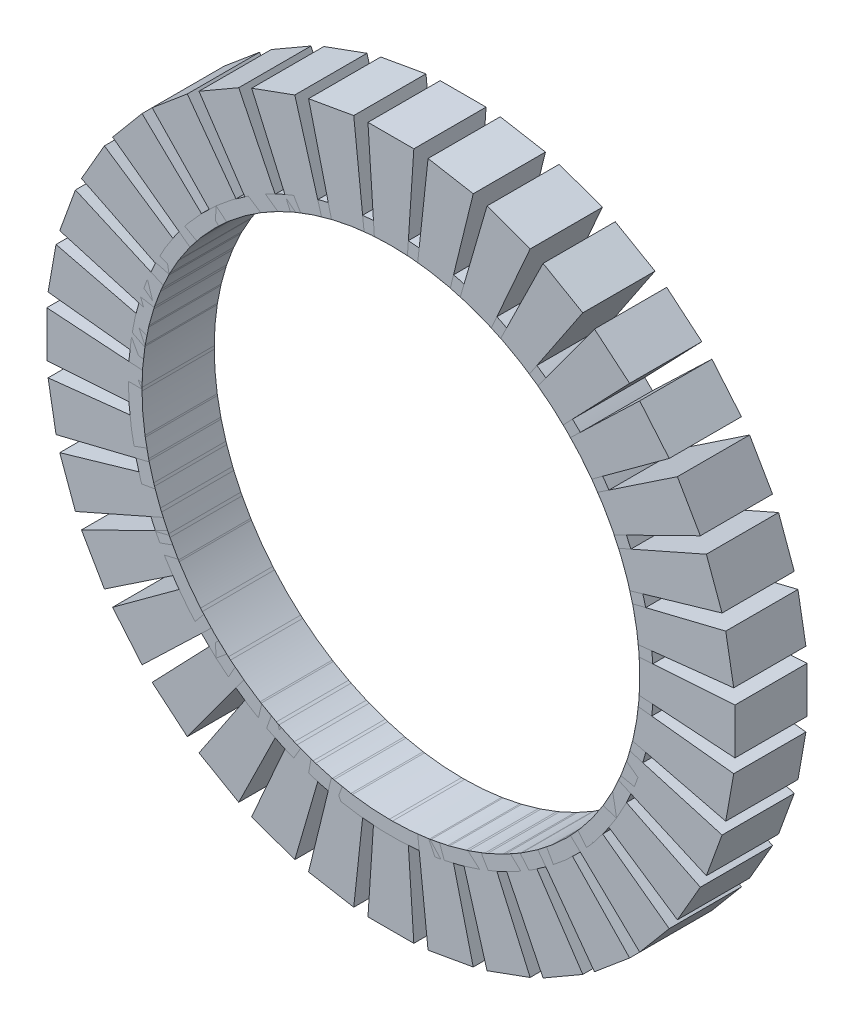
SolidWorks part; units mm, degrees
ref_plane "Front Plane" through (0, 0, 0) normal (0, 0, 1) x (1, 0, 0)
ref_plane "Top Plane" through (0, 0, 0) normal (0, 1, 0) x (1, 0, 0)
ref_plane "Right Plane" through (0, 0, 0) normal (1, 0, 0) x (0, 0, -1)
sketch "Sketch1" plane through (0, 0, 0) normal (0, 0, 1) x (1, 0, 0)
  line L0 (0, 0) -> (0, 40.5) construction
  line L1 (0, 0) -> (7.0328, 39.8847) construction
  line L2 (0, 0) -> (13.8518, 38.0576) construction
  line L3 (0, 0) -> (20.25, 35.074) construction
  line L4 (0, 0) -> (26.0329, 31.0248) construction
  line L5 (0, 0) -> (31.0248, 26.0329) construction
  line L6 (0, 0) -> (35.074, 20.25) construction
  line L7 (0, 0) -> (38.0576, 13.8518) construction
  line L8 (0, 0) -> (39.8847, 7.0328) construction
  line L9 (0, 0) -> (40.5, 0) construction
  line L10 (0, 0) -> (39.8847, -7.0328) construction
  line L11 (0, 0) -> (38.0576, -13.8518) construction
  line L12 (0, 0) -> (35.074, -20.25) construction
  line L13 (0, 0) -> (31.0248, -26.0329) construction
  line L14 (0, 0) -> (26.0329, -31.0248) construction
  line L15 (0, 0) -> (20.25, -35.074) construction
  line L16 (0, 0) -> (13.8518, -38.0576) construction
  line L17 (0, 0) -> (7.0328, -39.8847) construction
  line L18 (0, 0) -> (0, -40.5) construction
  line L19 (0, 0) -> (-7.0328, -39.8847) construction
  line L20 (0, 0) -> (-13.8518, -38.0576) construction
  line L21 (0, 0) -> (-20.25, -35.074) construction
  line L22 (0, 0) -> (-26.0329, -31.0248) construction
  line L23 (0, 0) -> (-31.0248, -26.0329) construction
  line L24 (0, 0) -> (-35.074, -20.25) construction
  line L25 (0, 0) -> (-38.0576, -13.8518) construction
  line L26 (0, 0) -> (-39.8847, -7.0328) construction
  line L27 (0, 0) -> (-40.5, 0) construction
  line L28 (0, 0) -> (-39.8847, 7.0328) construction
  line L29 (0, 0) -> (-38.0576, 13.8518) construction
  line L30 (0, 0) -> (-35.074, 20.25) construction
  line L31 (0, 0) -> (-31.0248, 26.0329) construction
  line L32 (0, 0) -> (-26.0329, 31.0248) construction
  line L33 (0, 0) -> (-20.25, 35.074) construction
  line L34 (0, 0) -> (-13.8518, 38.0576) construction
  line L35 (0, 0) -> (-7.0328, 39.8847) construction
  line L36 (-2.7, 40.5) -> (2.7, 40.5)
  line L37 (-1.949, 29.2351) -> (-2.7, 40.5)
  line L38 (1.949, 29.2351) -> (2.7, 40.5)
  line L39 (0, 0) -> (-1.949, 29.2351) construction
  line L40 (0, 0) -> (1.949, 29.2351) construction
  line L41 (3.1572, 29.1294) -> (4.3738, 40.3536)
  line L42 (6.996, 28.4525) -> (9.6917, 39.4159)
  line L43 (4.3738, 40.3536) -> (9.6917, 39.4159)
  line L44 (8.1675, 28.1386) -> (11.3146, 38.981)
  line L45 (11.8305, 26.8054) -> (16.389, 37.1341)
  line L46 (11.3146, 38.981) -> (16.389, 37.1341)
  line L47 (12.9297, 26.2928) -> (17.9117, 36.424)
  line L48 (16.3054, 24.3438) -> (22.5883, 33.724)
  line L49 (17.9117, 36.424) -> (22.5883, 33.724)
  line L50 (17.2989, 23.6482) -> (23.9646, 32.7603)
  line L51 (20.285, 21.1426) -> (28.1012, 29.2893)
  line L52 (23.9646, 32.7603) -> (28.1012, 29.2893)
  line L53 (21.1426, 20.285) -> (29.2893, 28.1012)
  line L54 (23.6482, 17.2989) -> (32.7603, 23.9646)
  line L55 (29.2893, 28.1012) -> (32.7603, 23.9646)
  line L56 (24.3438, 16.3054) -> (33.724, 22.5883)
  line L57 (26.2928, 12.9297) -> (36.424, 17.9117)
  line L58 (33.724, 22.5883) -> (36.424, 17.9117)
  line L59 (26.8054, 11.8305) -> (37.1341, 16.389)
  line L60 (28.1386, 8.1675) -> (38.981, 11.3146)
  line L61 (37.1341, 16.389) -> (38.981, 11.3146)
  line L62 (28.4525, 6.996) -> (39.4159, 9.6917)
  line L63 (29.1294, 3.1572) -> (40.3536, 4.3738)
  line L64 (39.4159, 9.6917) -> (40.3536, 4.3738)
  line L65 (29.2351, 1.949) -> (40.5, 2.7)
  line L66 (29.2351, -1.949) -> (40.5, -2.7)
  line L67 (40.5, 2.7) -> (40.5, -2.7)
  line L68 (29.1294, -3.1572) -> (40.3536, -4.3738)
  line L69 (28.4525, -6.996) -> (39.4159, -9.6917)
  line L70 (40.3536, -4.3738) -> (39.4159, -9.6917)
  line L71 (28.1386, -8.1675) -> (38.981, -11.3146)
  line L72 (26.8054, -11.8305) -> (37.1341, -16.389)
  line L73 (38.981, -11.3146) -> (37.1341, -16.389)
  line L74 (26.2928, -12.9297) -> (36.424, -17.9117)
  line L75 (24.3438, -16.3054) -> (33.724, -22.5883)
  line L76 (36.424, -17.9117) -> (33.724, -22.5883)
  line L77 (23.6482, -17.2989) -> (32.7603, -23.9646)
  line L78 (21.1426, -20.285) -> (29.2893, -28.1012)
  line L79 (32.7603, -23.9646) -> (29.2893, -28.1012)
  line L80 (20.285, -21.1426) -> (28.1012, -29.2893)
  line L81 (17.2989, -23.6482) -> (23.9646, -32.7603)
  line L82 (28.1012, -29.2893) -> (23.9646, -32.7603)
  line L83 (16.3054, -24.3438) -> (22.5883, -33.724)
  line L84 (12.9297, -26.2928) -> (17.9117, -36.424)
  line L85 (22.5883, -33.724) -> (17.9117, -36.424)
  line L86 (11.8305, -26.8054) -> (16.389, -37.1341)
  line L87 (8.1675, -28.1386) -> (11.3146, -38.981)
  line L88 (16.389, -37.1341) -> (11.3146, -38.981)
  line L89 (6.996, -28.4525) -> (9.6917, -39.4159)
  line L90 (3.1572, -29.1294) -> (4.3738, -40.3536)
  line L91 (9.6917, -39.4159) -> (4.3738, -40.3536)
  line L92 (1.949, -29.2351) -> (2.7, -40.5)
  line L93 (-1.949, -29.2351) -> (-2.7, -40.5)
  line L94 (2.7, -40.5) -> (-2.7, -40.5)
  line L95 (-3.1572, -29.1294) -> (-4.3738, -40.3536)
  line L96 (-6.996, -28.4525) -> (-9.6917, -39.4159)
  line L97 (-4.3738, -40.3536) -> (-9.6917, -39.4159)
  line L98 (-8.1675, -28.1386) -> (-11.3146, -38.981)
  line L99 (-11.8305, -26.8054) -> (-16.389, -37.1341)
  line L100 (-11.3146, -38.981) -> (-16.389, -37.1341)
  line L101 (-12.9297, -26.2928) -> (-17.9117, -36.424)
  line L102 (-16.3054, -24.3438) -> (-22.5883, -33.724)
  line L103 (-17.9117, -36.424) -> (-22.5883, -33.724)
  line L104 (-17.2989, -23.6482) -> (-23.9646, -32.7603)
  line L105 (-20.285, -21.1426) -> (-28.1012, -29.2893)
  line L106 (-23.9646, -32.7603) -> (-28.1012, -29.2893)
  line L107 (-21.1426, -20.285) -> (-29.2893, -28.1012)
  line L108 (-23.6482, -17.2989) -> (-32.7603, -23.9646)
  line L109 (-29.2893, -28.1012) -> (-32.7603, -23.9646)
  line L110 (-24.3438, -16.3054) -> (-33.724, -22.5883)
  line L111 (-26.2928, -12.9297) -> (-36.424, -17.9117)
  line L112 (-33.724, -22.5883) -> (-36.424, -17.9117)
  line L113 (-26.8054, -11.8305) -> (-37.1341, -16.389)
  line L114 (-28.1386, -8.1675) -> (-38.981, -11.3146)
  line L115 (-37.1341, -16.389) -> (-38.981, -11.3146)
  line L116 (-28.4525, -6.996) -> (-39.4159, -9.6917)
  line L117 (-29.1294, -3.1572) -> (-40.3536, -4.3738)
  line L118 (-39.4159, -9.6917) -> (-40.3536, -4.3738)
  line L119 (-29.2351, -1.949) -> (-40.5, -2.7)
  line L120 (-29.2351, 1.949) -> (-40.5, 2.7)
  line L121 (-40.5, -2.7) -> (-40.5, 2.7)
  line L122 (-29.1294, 3.1572) -> (-40.3536, 4.3738)
  line L123 (-28.4525, 6.996) -> (-39.4159, 9.6917)
  line L124 (-40.3536, 4.3738) -> (-39.4159, 9.6917)
  line L125 (-28.1386, 8.1675) -> (-38.981, 11.3146)
  line L126 (-26.8054, 11.8305) -> (-37.1341, 16.389)
  line L127 (-38.981, 11.3146) -> (-37.1341, 16.389)
  line L128 (-26.2928, 12.9297) -> (-36.424, 17.9117)
  line L129 (-24.3438, 16.3054) -> (-33.724, 22.5883)
  line L130 (-36.424, 17.9117) -> (-33.724, 22.5883)
  line L131 (-23.6482, 17.2989) -> (-32.7603, 23.9646)
  line L132 (-21.1426, 20.285) -> (-29.2893, 28.1012)
  line L133 (-32.7603, 23.9646) -> (-29.2893, 28.1012)
  line L134 (-20.285, 21.1426) -> (-28.1012, 29.2893)
  line L135 (-17.2989, 23.6482) -> (-23.9646, 32.7603)
  line L136 (-28.1012, 29.2893) -> (-23.9646, 32.7603)
  line L137 (-16.3054, 24.3438) -> (-22.5883, 33.724)
  line L138 (-12.9297, 26.2928) -> (-17.9117, 36.424)
  line L139 (-22.5883, 33.724) -> (-17.9117, 36.424)
  line L140 (-11.8305, 26.8054) -> (-16.389, 37.1341)
  line L141 (-8.1675, 28.1386) -> (-11.3146, 38.981)
  line L142 (-16.389, 37.1341) -> (-11.3146, 38.981)
  line L143 (-6.996, 28.4525) -> (-9.6917, 39.4159)
  line L144 (-3.1572, 29.1294) -> (-4.3738, 40.3536)
  line L145 (-9.6917, 39.4159) -> (-4.3738, 40.3536)
  arc A0 (-18.8337, 22.4451) -> (14.65, 25.3745) centre (0, 0) ccw construction
  circle A1 centre (0, 0) radius 40.5 construction
  arc A2 (-1.949, 29.2351) -> (-5.0879, 28.8549) centre (0, 0) ccw construction
  arc A3 (-5.0879, 28.8549) -> (-10.0212, 27.533) centre (0, 0) ccw construction
  arc A4 (-10.0212, 27.533) -> (-14.65, 25.3745) centre (0, 0) ccw construction
  arc A5 (-14.65, 25.3745) -> (-18.8337, 22.4451) centre (0, 0) ccw construction
  arc A6 (14.65, 25.3745) -> (10.0212, 27.533) centre (0, 0) ccw construction
  arc A7 (1.949, 29.2351) -> (-1.949, 29.2351) centre (0, 0) ccw
  arc A8 (10.0212, 27.533) -> (5.0879, 28.8549) centre (0, 0) ccw construction
  arc A9 (5.0879, 28.8549) -> (1.949, 29.2351) centre (0, 0) ccw construction
  arc A10 (6.996, 28.4525) -> (3.1572, 29.1294) centre (0, 0) ccw
  arc A11 (11.8305, 26.8054) -> (8.1675, 28.1386) centre (0, 0) ccw
  arc A12 (16.3054, 24.3438) -> (12.9297, 26.2928) centre (0, 0) ccw
  arc A13 (20.285, 21.1426) -> (17.2989, 23.6482) centre (0, 0) ccw
  arc A14 (23.6482, 17.2989) -> (21.1426, 20.285) centre (0, 0) ccw
  arc A15 (26.2928, 12.9297) -> (24.3438, 16.3054) centre (0, 0) ccw
  arc A16 (28.1386, 8.1675) -> (26.8054, 11.8305) centre (0, 0) ccw
  arc A17 (29.1294, 3.1572) -> (28.4525, 6.996) centre (0, 0) ccw
  arc A18 (29.2351, -1.949) -> (29.2351, 1.949) centre (0, 0) ccw
  arc A19 (28.4525, -6.996) -> (29.1294, -3.1572) centre (0, 0) ccw
  arc A20 (26.8054, -11.8305) -> (28.1386, -8.1675) centre (0, 0) ccw
  arc A21 (24.3438, -16.3054) -> (26.2928, -12.9297) centre (0, 0) ccw
  arc A22 (21.1426, -20.285) -> (23.6482, -17.2989) centre (0, 0) ccw
  arc A23 (17.2989, -23.6482) -> (20.285, -21.1426) centre (0, 0) ccw
  arc A24 (12.9297, -26.2928) -> (16.3054, -24.3438) centre (0, 0) ccw
  arc A25 (8.1675, -28.1386) -> (11.8305, -26.8054) centre (0, 0) ccw
  arc A26 (3.1572, -29.1294) -> (6.996, -28.4525) centre (0, 0) ccw
  arc A27 (-1.949, -29.2351) -> (1.949, -29.2351) centre (0, 0) ccw
  arc A28 (-6.996, -28.4525) -> (-3.1572, -29.1294) centre (0, 0) ccw
  arc A29 (-11.8305, -26.8054) -> (-8.1675, -28.1386) centre (0, 0) ccw
  arc A30 (-16.3054, -24.3438) -> (-12.9297, -26.2928) centre (0, 0) ccw
  arc A31 (-20.285, -21.1426) -> (-17.2989, -23.6482) centre (0, 0) ccw
  arc A32 (-23.6482, -17.2989) -> (-21.1426, -20.285) centre (0, 0) ccw
  arc A33 (-26.2928, -12.9297) -> (-24.3438, -16.3054) centre (0, 0) ccw
  arc A34 (-28.1386, -8.1675) -> (-26.8054, -11.8305) centre (0, 0) ccw
  arc A35 (-29.1294, -3.1572) -> (-28.4525, -6.996) centre (0, 0) ccw
  arc A36 (-29.2351, 1.949) -> (-29.2351, -1.949) centre (0, 0) ccw
  arc A37 (-28.4525, 6.996) -> (-29.1294, 3.1572) centre (0, 0) ccw
  arc A38 (-26.8054, 11.8305) -> (-28.1386, 8.1675) centre (0, 0) ccw
  arc A39 (-24.3438, 16.3054) -> (-26.2928, 12.9297) centre (0, 0) ccw
  arc A40 (-21.1426, 20.285) -> (-23.6482, 17.2989) centre (0, 0) ccw
  arc A41 (-17.2989, 23.6482) -> (-20.285, 21.1426) centre (0, 0) ccw
  arc A42 (-12.9297, 26.2928) -> (-16.3054, 24.3438) centre (0, 0) ccw
  arc A43 (-8.1675, 28.1386) -> (-11.8305, 26.8054) centre (0, 0) ccw
  arc A44 (-3.1572, 29.1294) -> (-6.996, 28.4525) centre (0, 0) ccw
  circle A45 centre (0, 0) radius 29.3 construction
  circle A46 centre (0, 0) radius 30.9 construction
  point P42 (0, 0)
  point P43 (0, 40.5)
  point P194 (0, 0)
  dimension "D1" = 58.6
  dimension "D2" = 81
  dimension "D6" = 61.8
  dimension "D3" = 36
  dimension "D4" = 5.4
  dimension "D5" = 36
extrude "Boss-Extrude1" add sketch "Sketch1" along normal mid plane 8.5
sketch "Sketch2" plane through (0, 0, 0) normal (0, 0, 1) x (1, 0, 0)
  circle A0 centre (0, 0) radius 29.3
  circle A1 centre (0, 0) radius 30.9
  dimension "D1" = 58.6
  dimension "D2" = 61.8
extrude "Boss-Extrude2" add sketch "Sketch2" along normal mid plane 8.5 separate body
